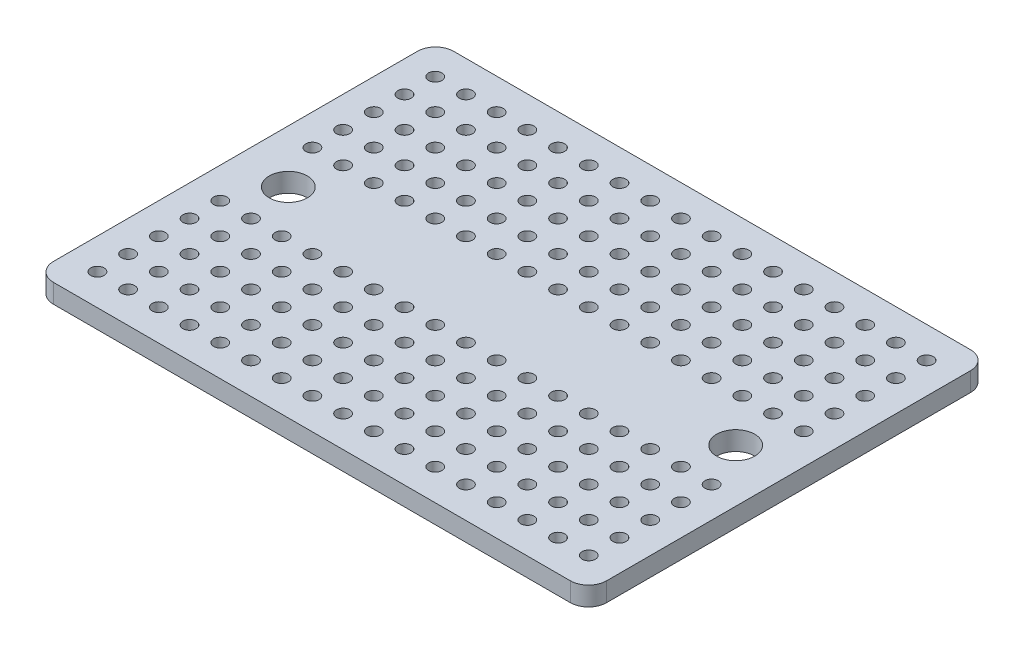
SolidWorks part; units mm, degrees
ref_plane "Front Plane" through (0, 0, 0) normal (0, 0, 1) x (1, 0, 0)
ref_plane "Top Plane" through (0, 0, 0) normal (0, 1, 0) x (1, 0, 0)
ref_plane "Right Plane" through (0, 0, 0) normal (1, 0, 0) x (0, 0, -1)
sketch "Sketch1" plane through (0, 0, 0) normal (0, 1, 0) x (1, 0, 0)
  line L0 (-22.875, 0) -> (22.875, 0) construction
  line L1 (-22.875, 16.55) -> (22.875, 16.55)
  line L2 (-22.875, 16.55) -> (-22.875, -16.55)
  line L3 (-22.875, -16.55) -> (22.875, -16.55)
  line L4 (22.875, 16.55) -> (22.875, -16.55)
  line L5 (-22.875, 16.55) -> (22.875, -16.55) construction
  line L6 (-22.875, -16.55) -> (22.875, 16.55) construction
  line L7 (0, 16.55) -> (0, -16.55) construction
  line L8 (-22.875, 13.97) -> (22.875, 13.97) construction
  line L9 (-20.32, 3.81) -> (-20.32, 0) construction
  line L10 (-20.32, 0) -> (-20.32, -3.81) construction
  line L11 (-20.32, 14.52) -> (-22.875, 14.52) construction
  line L12 (20.32, 14.52) -> (22.875, 14.52) construction
  line L13 (-20.32, 13.97) -> (-20.32, 11.43) construction
  line L14 (-20.32, 11.43) -> (-17.78, 11.43) construction
  circle A0 centre (-18.5, 0) radius 1.575
  circle A1 centre (18.5, 0) radius 1.575
  circle A2 centre (-20.32, 13.97) radius 0.55
  circle A3 centre (-17.78, 13.97) radius 0.55
  circle A4 centre (-15.24, 13.97) radius 0.55
  circle A5 centre (-12.7, 13.97) radius 0.55
  circle A6 centre (-10.16, 13.97) radius 0.55
  circle A7 centre (-7.62, 13.97) radius 0.55
  circle A8 centre (-5.08, 13.97) radius 0.55
  circle A9 centre (-2.54, 13.97) radius 0.55
  circle A10 centre (0, 13.97) radius 0.55
  circle A11 centre (2.54, 13.97) radius 0.55
  circle A12 centre (5.08, 13.97) radius 0.55
  circle A13 centre (7.62, 13.97) radius 0.55
  circle A14 centre (10.16, 13.97) radius 0.55
  circle A15 centre (12.7, 13.97) radius 0.55
  circle A16 centre (15.24, 13.97) radius 0.55
  circle A17 centre (17.78, 13.97) radius 0.55
  circle A18 centre (20.32, 13.97) radius 0.55
  circle A19 centre (-17.78, 11.43) radius 0.55
  circle A20 centre (-15.24, 11.43) radius 0.55
  circle A21 centre (-12.7, 11.43) radius 0.55
  circle A22 centre (-10.16, 11.43) radius 0.55
  circle A23 centre (-7.62, 11.43) radius 0.55
  circle A24 centre (-5.08, 11.43) radius 0.55
  circle A25 centre (-2.54, 11.43) radius 0.55
  circle A26 centre (0, 11.43) radius 0.55
  circle A27 centre (2.54, 11.43) radius 0.55
  circle A28 centre (5.08, 11.43) radius 0.55
  circle A29 centre (7.62, 11.43) radius 0.55
  circle A30 centre (10.16, 11.43) radius 0.55
  circle A31 centre (12.7, 11.43) radius 0.55
  circle A32 centre (15.24, 11.43) radius 0.55
  circle A33 centre (17.78, 11.43) radius 0.55
  circle A34 centre (20.32, 11.43) radius 0.55
  circle A35 centre (-17.78, 8.89) radius 0.55
  circle A36 centre (-15.24, 8.89) radius 0.55
  circle A37 centre (-12.7, 8.89) radius 0.55
  circle A38 centre (-10.16, 8.89) radius 0.55
  circle A39 centre (-7.62, 8.89) radius 0.55
  circle A40 centre (-5.08, 8.89) radius 0.55
  circle A41 centre (-2.54, 8.89) radius 0.55
  circle A42 centre (0, 8.89) radius 0.55
  circle A43 centre (2.54, 8.89) radius 0.55
  circle A44 centre (5.08, 8.89) radius 0.55
  circle A45 centre (7.62, 8.89) radius 0.55
  circle A46 centre (10.16, 8.89) radius 0.55
  circle A47 centre (12.7, 8.89) radius 0.55
  circle A48 centre (15.24, 8.89) radius 0.55
  circle A49 centre (17.78, 8.89) radius 0.55
  circle A50 centre (20.32, 8.89) radius 0.55
  circle A51 centre (-17.78, 6.35) radius 0.55
  circle A52 centre (-15.24, 6.35) radius 0.55
  circle A53 centre (-12.7, 6.35) radius 0.55
  circle A54 centre (-10.16, 6.35) radius 0.55
  circle A55 centre (-7.62, 6.35) radius 0.55
  circle A56 centre (-5.08, 6.35) radius 0.55
  circle A57 centre (-2.54, 6.35) radius 0.55
  circle A58 centre (0, 6.35) radius 0.55
  circle A59 centre (2.54, 6.35) radius 0.55
  circle A60 centre (5.08, 6.35) radius 0.55
  circle A61 centre (7.62, 6.35) radius 0.55
  circle A62 centre (10.16, 6.35) radius 0.55
  circle A63 centre (12.7, 6.35) radius 0.55
  circle A64 centre (15.24, 6.35) radius 0.55
  circle A65 centre (17.78, 6.35) radius 0.55
  circle A66 centre (20.32, 6.35) radius 0.55
  circle A67 centre (-17.78, 3.81) radius 0.55
  circle A68 centre (-15.24, 3.81) radius 0.55
  circle A69 centre (-12.7, 3.81) radius 0.55
  circle A70 centre (-10.16, 3.81) radius 0.55
  circle A71 centre (-7.62, 3.81) radius 0.55
  circle A72 centre (-5.08, 3.81) radius 0.55
  circle A73 centre (-2.54, 3.81) radius 0.55
  circle A74 centre (0, 3.81) radius 0.55
  circle A75 centre (2.54, 3.81) radius 0.55
  circle A76 centre (5.08, 3.81) radius 0.55
  circle A77 centre (7.62, 3.81) radius 0.55
  circle A78 centre (10.16, 3.81) radius 0.55
  circle A79 centre (12.7, 3.81) radius 0.55
  circle A80 centre (15.24, 3.81) radius 0.55
  circle A81 centre (17.78, 3.81) radius 0.55
  circle A82 centre (20.32, 3.81) radius 0.55
  circle A115 centre (-17.78, -3.81) radius 0.55
  circle A116 centre (-15.24, -3.81) radius 0.55
  circle A117 centre (-12.7, -3.81) radius 0.55
  circle A118 centre (-10.16, -3.81) radius 0.55
  circle A119 centre (-7.62, -3.81) radius 0.55
  circle A120 centre (-5.08, -3.81) radius 0.55
  circle A121 centre (-2.54, -3.81) radius 0.55
  circle A122 centre (0, -3.81) radius 0.55
  circle A123 centre (2.54, -3.81) radius 0.55
  circle A124 centre (5.08, -3.81) radius 0.55
  circle A125 centre (7.62, -3.81) radius 0.55
  circle A126 centre (10.16, -3.81) radius 0.55
  circle A127 centre (12.7, -3.81) radius 0.55
  circle A128 centre (15.24, -3.81) radius 0.55
  circle A129 centre (17.78, -3.81) radius 0.55
  circle A130 centre (20.32, -3.81) radius 0.55
  circle A131 centre (-17.78, -6.35) radius 0.55
  circle A132 centre (-15.24, -6.35) radius 0.55
  circle A133 centre (-12.7, -6.35) radius 0.55
  circle A134 centre (-10.16, -6.35) radius 0.55
  circle A135 centre (-7.62, -6.35) radius 0.55
  circle A136 centre (-5.08, -6.35) radius 0.55
  circle A137 centre (-2.54, -6.35) radius 0.55
  circle A138 centre (0, -6.35) radius 0.55
  circle A139 centre (2.54, -6.35) radius 0.55
  circle A140 centre (5.08, -6.35) radius 0.55
  circle A141 centre (7.62, -6.35) radius 0.55
  circle A142 centre (10.16, -6.35) radius 0.55
  circle A143 centre (12.7, -6.35) radius 0.55
  circle A144 centre (15.24, -6.35) radius 0.55
  circle A145 centre (17.78, -6.35) radius 0.55
  circle A146 centre (20.32, -6.35) radius 0.55
  circle A147 centre (-17.78, -8.89) radius 0.55
  circle A148 centre (-15.24, -8.89) radius 0.55
  circle A149 centre (-12.7, -8.89) radius 0.55
  circle A150 centre (-10.16, -8.89) radius 0.55
  circle A151 centre (-7.62, -8.89) radius 0.55
  circle A152 centre (-5.08, -8.89) radius 0.55
  circle A153 centre (-2.54, -8.89) radius 0.55
  circle A154 centre (0, -8.89) radius 0.55
  circle A155 centre (2.54, -8.89) radius 0.55
  circle A156 centre (5.08, -8.89) radius 0.55
  circle A157 centre (7.62, -8.89) radius 0.55
  circle A158 centre (10.16, -8.89) radius 0.55
  circle A159 centre (12.7, -8.89) radius 0.55
  circle A160 centre (15.24, -8.89) radius 0.55
  circle A161 centre (17.78, -8.89) radius 0.55
  circle A162 centre (20.32, -8.89) radius 0.55
  circle A163 centre (-17.78, -11.43) radius 0.55
  circle A164 centre (-15.24, -11.43) radius 0.55
  circle A165 centre (-12.7, -11.43) radius 0.55
  circle A166 centre (-10.16, -11.43) radius 0.55
  circle A167 centre (-7.62, -11.43) radius 0.55
  circle A168 centre (-5.08, -11.43) radius 0.55
  circle A169 centre (-2.54, -11.43) radius 0.55
  circle A170 centre (0, -11.43) radius 0.55
  circle A171 centre (2.54, -11.43) radius 0.55
  circle A172 centre (5.08, -11.43) radius 0.55
  circle A173 centre (7.62, -11.43) radius 0.55
  circle A174 centre (10.16, -11.43) radius 0.55
  circle A175 centre (12.7, -11.43) radius 0.55
  circle A176 centre (15.24, -11.43) radius 0.55
  circle A177 centre (17.78, -11.43) radius 0.55
  circle A178 centre (20.32, -11.43) radius 0.55
  circle A179 centre (-17.78, -13.97) radius 0.55
  circle A180 centre (-15.24, -13.97) radius 0.55
  circle A181 centre (-12.7, -13.97) radius 0.55
  circle A182 centre (-10.16, -13.97) radius 0.55
  circle A183 centre (-7.62, -13.97) radius 0.55
  circle A184 centre (-5.08, -13.97) radius 0.55
  circle A185 centre (-2.54, -13.97) radius 0.55
  circle A186 centre (0, -13.97) radius 0.55
  circle A187 centre (2.54, -13.97) radius 0.55
  circle A188 centre (5.08, -13.97) radius 0.55
  circle A189 centre (7.62, -13.97) radius 0.55
  circle A190 centre (10.16, -13.97) radius 0.55
  circle A191 centre (12.7, -13.97) radius 0.55
  circle A192 centre (15.24, -13.97) radius 0.55
  circle A193 centre (17.78, -13.97) radius 0.55
  circle A194 centre (20.32, -13.97) radius 0.55
  circle A195 centre (-20.32, 11.43) radius 0.55
  circle A196 centre (-20.32, 8.89) radius 0.55
  circle A197 centre (-20.32, 6.35) radius 0.55
  circle A198 centre (-20.32, 3.81) radius 0.55
  circle A201 centre (-20.32, -3.81) radius 0.55
  circle A202 centre (-20.32, -6.35) radius 0.55
  circle A203 centre (-20.32, -8.89) radius 0.55
  circle A204 centre (-20.32, -11.43) radius 0.55
  circle A205 centre (-20.32, -13.97) radius 0.55
  circle A206 centre (-17.78, 1.27) radius 0.55 [skipped]
  circle A207 centre (-15.24, 1.27) radius 0.55 [skipped]
  circle A208 centre (-12.7, 1.27) radius 0.55 [skipped]
  circle A209 centre (-10.16, 1.27) radius 0.55 [skipped]
  circle A210 centre (-7.62, 1.27) radius 0.55 [skipped]
  circle A211 centre (-5.08, 1.27) radius 0.55 [skipped]
  circle A212 centre (-2.54, 1.27) radius 0.55 [skipped]
  circle A213 centre (0, 1.27) radius 0.55 [skipped]
  circle A214 centre (2.54, 1.27) radius 0.55 [skipped]
  circle A215 centre (5.08, 1.27) radius 0.55 [skipped]
  circle A216 centre (7.62, 1.27) radius 0.55 [skipped]
  circle A217 centre (10.16, 1.27) radius 0.55 [skipped]
  circle A218 centre (12.7, 1.27) radius 0.55 [skipped]
  circle A219 centre (15.24, 1.27) radius 0.55 [skipped]
  circle A220 centre (17.78, 1.27) radius 0.55 [skipped]
  circle A221 centre (20.32, 1.27) radius 0.55 [skipped]
  circle A222 centre (-17.78, -1.27) radius 0.55 [skipped]
  circle A223 centre (-15.24, -1.27) radius 0.55 [skipped]
  circle A224 centre (-12.7, -1.27) radius 0.55 [skipped]
  circle A225 centre (-10.16, -1.27) radius 0.55 [skipped]
  circle A226 centre (-7.62, -1.27) radius 0.55 [skipped]
  circle A227 centre (-5.08, -1.27) radius 0.55 [skipped]
  circle A228 centre (-2.54, -1.27) radius 0.55 [skipped]
  circle A229 centre (0, -1.27) radius 0.55 [skipped]
  circle A230 centre (2.54, -1.27) radius 0.55 [skipped]
  circle A231 centre (5.08, -1.27) radius 0.55 [skipped]
  circle A232 centre (7.62, -1.27) radius 0.55 [skipped]
  circle A233 centre (10.16, -1.27) radius 0.55 [skipped]
  circle A234 centre (12.7, -1.27) radius 0.55 [skipped]
  circle A235 centre (15.24, -1.27) radius 0.55 [skipped]
  circle A236 centre (17.78, -1.27) radius 0.55 [skipped]
  circle A237 centre (20.32, -1.27) radius 0.55 [skipped]
  circle A238 centre (-20.32, 1.27) radius 0.55 [skipped]
  circle A239 centre (-20.32, -1.27) radius 0.55 [skipped]
  point P0 (0, 0)
  point P180 (-20.32, 3.6954)
  point P181 (-20.32, -3.7535)
  dimension "D4" = 3.15
  dimension "D5" = 1.1
  dimension "D1" = 45.75
  dimension "D2" = 33.1
  dimension "D3" = 37
  dimension "D8" = 2.54
  dimension "D6" = 17
  dimension "D7" = 12
extrude "Boss-Extrude1" add sketch "Sketch1" along normal blind 1.57
fillet "Fillet1" radius 1.5 4 edges at (-22.875, 0.785, -16.55) (22.875, 0.785, -16.55) (-22.875, 0.785, 16.55) (22.875, 0.785, 16.55)
